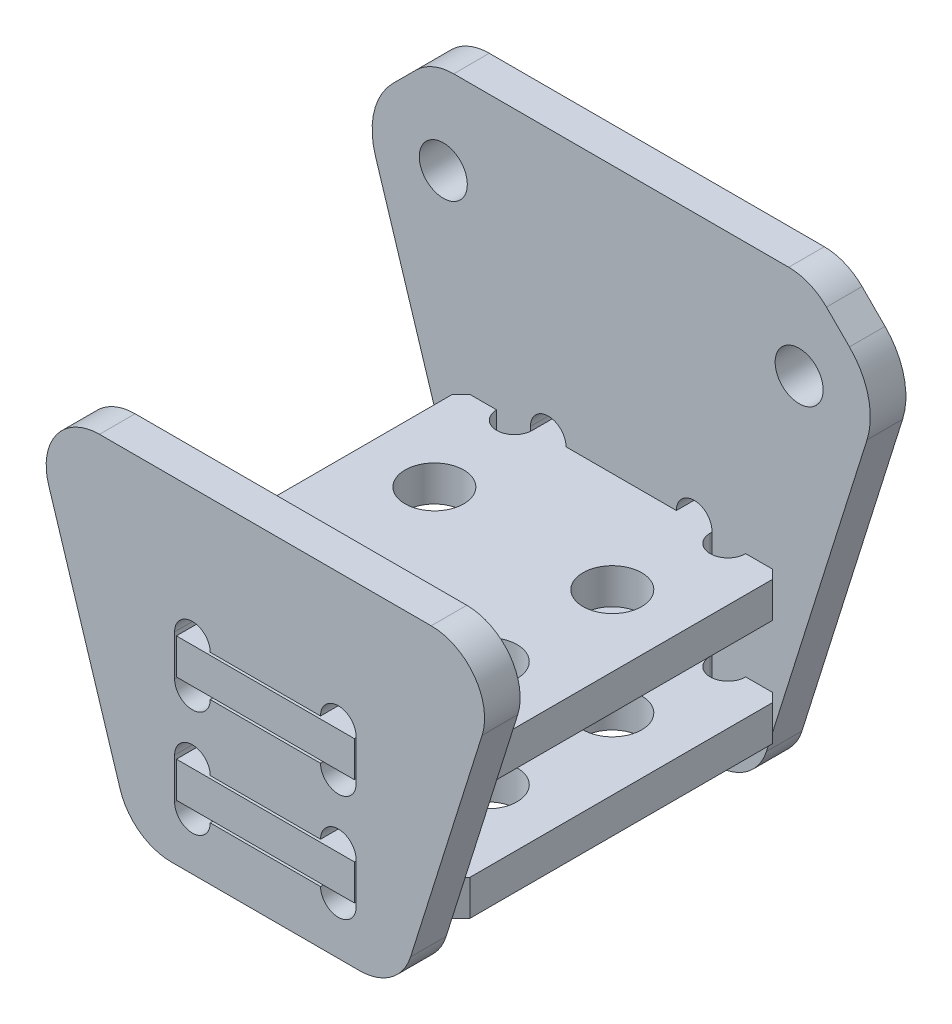
SolidWorks part; units mm, degrees
material "碳板"
ref_plane "前视基准面" through (0, 0, 0) normal (0, 0, 1) x (1, 0, 0)
ref_plane "上视基准面" through (0, 0, 0) normal (0, 1, 0) x (1, 0, 0)
ref_plane "右视基准面" through (0, 0, 0) normal (1, 0, 0) x (0, 0, -1)
sketch "草图1" plane through (0, 0, 0) normal (0, 0, 1) x (1, 0, 0)
  line L0 (0, 31.7086) -> (0, -23.8875) construction
  line L1 (-38.4461, 0) -> (36.9384, 0) construction
  line L2 (-12.8284, 2.8284) -> (-10.6569, 5)
  line L3 (-10.6569, 5) -> (10.6569, 5)
  line L4 (-5.1, -16) -> (-5.1, -18.3)
  line L5 (-5.1, -10) -> (5.1, -10)
  line L6 (-5.1, -10) -> (-5.1, -12.3)
  line L7 (-5.1, -12.3) -> (5.1, -12.3)
  line L8 (5.1, -10) -> (5.1, -12.3)
  line L9 (-5.1, -10) -> (5.1, -12.3) construction
  line L10 (-5.1, -12.3) -> (5.1, -10) construction
  line L11 (-5.1, -16) -> (5.1, -16)
  line L12 (5.1, -16) -> (5.1, -18.3)
  line L13 (-5.1, -18.3) -> (5.1, -18.3)
  line L14 (-4.1, -10) -> (-4.1, -16) construction
  line L15 (-13.8161, -1.1991) -> (-7.5, -21.3)
  line L16 (-7.5, -21.3) -> (7.5, -21.3)
  line L17 (13.8161, -1.1991) -> (7.5, -21.3)
  line L18 (12.8284, 2.8284) -> (10.6569, 5)
  circle A0 centre (-10, 0) radius 1.35
  circle A1 centre (10, 0) radius 1.35
  arc A2 (-12.8284, 2.8284) -> (-13.8161, -1.1991) centre (-10, 0) ccw
  circle A3 centre (-4.1, -10) radius 1
  circle A4 centre (-4.1, -12.3) radius 1
  circle A5 centre (4.1, -10) radius 1
  circle A6 centre (4.1, -12.3) radius 1
  circle A7 centre (-4.1, -16) radius 1
  circle A8 centre (-4.1, -18.3) radius 1
  circle A9 centre (4.1, -16) radius 1
  circle A10 centre (4.1, -18.3) radius 1
  arc A11 (12.8284, 2.8284) -> (13.8161, -1.1991) centre (10, 0) cw
  point P13 (0, -11.15)
  point P42 (0, -21.3)
  point P46 (0, 5)
  dimension "D1" = 2.7
  dimension "D3" = 5
  dimension "D4" = 2
  dimension "D10" = 4
  dimension "D2" = 20
  dimension "D5" = 2.3
  dimension "D6" = 10.2
  dimension "D7" = 10
  dimension "D9" = 6
  dimension "D11" = 3
  dimension "D12" = 15
  dimension "D13" = 135
  dimension "D8" = 2
extrude "凸台-拉伸1" add sketch "草图1" along normal blind 2 contours A11 L18 L3 L2 A2 L15 L16 L17 A10 L13 A8 L4 A7 L11 A9 L12 A6 L7 A4 L6 A3 L5 A5 L8 A0 A1
fillet "圆角1" radius 3 4 edges at (-10.6569, 5, 1) (10.6569, 5, 1) (7.5, -21.3, 1) (-7.5, -21.3, 1)
ref_plane "基准面1" through (0, -11.15, 0) normal (0, -1, 0) x (-1, 0, 0)
sketch "草图2" plane through (0, -11.15, 0) normal (0, -1, 0) x (-1, 0, 0)
  line L0 (3.1, 0) -> (-3.1, 0) construction
  line L1 (3.1, 0) -> (-3.1, 0) construction
  line L2 (3.1, -2) -> (-3.1, -2) construction
  line L3 (3.1, -2) -> (-3.1, -2) construction
  line L4 (0, 0) -> (0, -2) construction
  line L5 (5, -2) -> (5, 0)
  line L6 (5, 0) -> (-5, 0)
  line L7 (7, -2) -> (9, -2)
  line L8 (9, -2) -> (9, -20)
  line L9 (9, -11) -> (-19.4503, -11) construction
  line L10 (-9, -2) -> (-9, -20)
  line L11 (-7, -2) -> (-9, -2)
  line L12 (-5, -2) -> (-5, 0)
  line L13 (-7, -20) -> (-9, -20)
  line L14 (-5, -20) -> (-5, -22)
  line L15 (5, -22) -> (-5, -22)
  line L16 (5, -20) -> (5, -22)
  line L17 (7, -20) -> (9, -20)
  arc A0 (5, -2) -> (7, -2) centre (6, -2) ccw
  arc A1 (-5, -2) -> (-7, -2) centre (-6, -2) cw
  arc A2 (-5, -20) -> (-7, -20) centre (-6, -20) ccw
  arc A3 (5, -20) -> (7, -20) centre (6, -20) cw
  circle A4 centre (-5, -7.5) radius 1.65
  circle A5 centre (-5, -14.5) radius 1.65
  circle A6 centre (5, -14.5) radius 1.65
  circle A7 centre (5, -7.5) radius 1.65
  point P21 (-9, -11)
  dimension "D2" = 2
  dimension "D5" = 3.3
  dimension "D1" = 10
  dimension "D3" = 2
  dimension "D4" = 18
  dimension "D6" = 7
  dimension "D7" = 4
extrude "凸台-拉伸2" add sketch "草图2" along normal mid plane 2 separate body
chamfer "倒角1" distance 0.5 angle 45 4 edges at (-9, -11.15, 2) (9, -11.15, 2) (9, -11.15, 20) (-9, -11.15, 20)
pattern_linear "阵列(线性)1" count 2 spacing 6 along (0, -1, 0) of bodies 107
sketch "草图3" plane through (0, 0, 22) normal (0, 0, 1) x (1, 0, 0)
  line L0 (5, -10.15) -> (-5, -10.15) construction
  line L1 (0, -10.15) -> (0, -18.15) construction
  line L2 (5, -18.15) -> (-5, -18.15) construction
  line L3 (0, -14.15) -> (13.0131, -14.15) construction
  line L4 (-5, -11.15) -> (5, -11.15) construction
  line L5 (-5, -12.15) -> (-5, -10.15) construction
  line L6 (5, -12.15) -> (5, -10.15) construction
  line L7 (-5.1, -18.3) -> (-5.1, -16)
  line L8 (-3.1, -10) -> (3.1, -10)
  line L9 (-5.1, -10) -> (-5.1, -12.3)
  line L10 (-3.1, -12.3) -> (3.1, -12.3)
  line L11 (5.1, -10) -> (5.1, -12.3)
  line L12 (-5.1, -10) -> (5.1, -12.3) construction
  line L13 (-5.1, -12.3) -> (5.1, -10) construction
  line L14 (-3.1, -18.3) -> (3.1, -18.3)
  line L15 (5.1, -18.3) -> (5.1, -16)
  line L16 (-3.1, -16) -> (3.1, -16)
  line L17 (-5.298, -21.3) -> (5.298, -21.3) construction
  line L18 (-5.298, -21.3) -> (5.298, -21.3)
  line L19 (-13.8161, -1.1991) -> (-8.1601, -19.1993) construction
  line L20 (-13.4073, -2.5) -> (-8.1601, -19.1993)
  line L21 (13.8161, -1.1991) -> (8.1601, -19.1993) construction
  line L22 (13.4073, -2.5) -> (8.1601, -19.1993)
  line L23 (-13.4073, -2.5) -> (13.4073, -2.5)
  line L24 (-15.8895, 0) -> (24.7812, 0) construction
  arc A0 (-3.1, -10) -> (-5.1, -10) centre (-4.1, -10) ccw
  arc A1 (-5.1, -12.3) -> (-3.1, -12.3) centre (-4.1, -12.3) ccw
  arc A2 (5.1, -10) -> (3.1, -10) centre (4.1, -10) ccw
  arc A3 (3.1, -12.3) -> (5.1, -12.3) centre (4.1, -12.3) ccw
  arc A4 (-5.1, -16) -> (-3.1, -16) centre (-4.1, -16) cw
  arc A5 (-3.1, -18.3) -> (-5.1, -18.3) centre (-4.1, -18.3) cw
  arc A6 (5.1, -18.3) -> (3.1, -18.3) centre (4.1, -18.3) cw
  arc A7 (3.1, -16) -> (5.1, -16) centre (4.1, -16) cw
  arc A8 (-8.1601, -19.1993) -> (-5.298, -21.3) centre (-5.298, -18.3) ccw construction
  arc A9 (-8.1601, -19.1993) -> (-5.298, -21.3) centre (-5.298, -18.3) ccw
  arc A10 (5.298, -21.3) -> (8.1601, -19.1993) centre (5.298, -18.3) ccw construction
  arc A11 (5.298, -21.3) -> (8.1601, -19.1993) centre (5.298, -18.3) ccw
  point P14 (0, -11.15)
  dimension "D3" = 2
  dimension "D1" = 10.2
  dimension "D2" = 2.3
  dimension "D4" = 2.5
extrude "凸台-拉伸3" add sketch "草图3" against normal blind 2 separate body
fillet "圆角2" radius 3 2 edges at (-13.4073, -2.5, 21) (13.4073, -2.5, 21)
